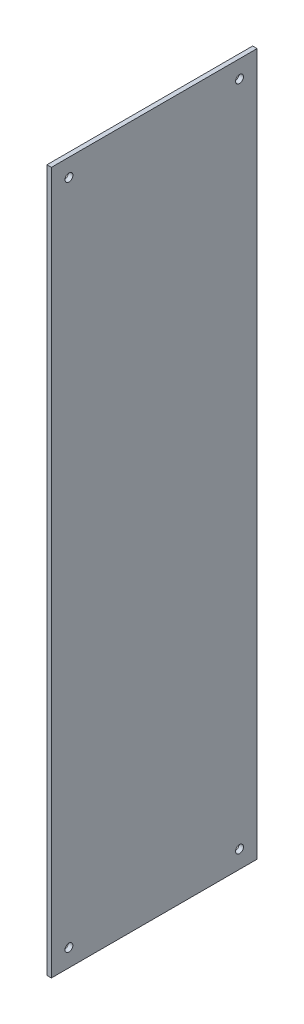
SolidWorks part; units mm, degrees
ref_plane "Front Plane" through (0, 0, 0) normal (1, 0, 0) x (0, 1, 0)
ref_plane "Top Plane" through (0, 0, 0) normal (0, 0, 1) x (0, 1, 0)
ref_plane "Right Plane" through (0, 0, 0) normal (0, 1, 0) x (-1, 0, 0)
sketch "Sketch1" plane through (0, 0, 0) normal (1, 0, 0) x (0, 1, 0)
  line L1 (-250, -73.25) -> (250, -73.25)
  line L2 (-250, -73.25) -> (-250, 73.25)
  line L3 (-250, 73.25) -> (250, 73.25)
  line L4 (250, -73.25) -> (250, 73.25)
  line L5 (-250, -73.25) -> (250, 73.25) construction
  line L6 (-250, 73.25) -> (250, -73.25) construction
  line L7 (237.5, -60.75) -> (-237.5, -60.75) construction
  line L8 (237.5, -60.75) -> (237.5, 60.75) construction
  line L9 (237.5, 60.75) -> (-237.5, 60.75) construction
  line L10 (-237.5, -60.75) -> (-237.5, 60.75) construction
  line L11 (237.5, -60.75) -> (-237.5, 60.75) construction
  line L12 (237.5, 60.75) -> (-237.5, -60.75) construction
  circle A0 centre (-237.5, 60.75) radius 2.8
  circle A1 centre (-237.5, -60.75) radius 2.8
  circle A2 centre (237.5, 60.75) radius 2.8
  circle A3 centre (237.5, -60.75) radius 2.8
  point P0 (0, 0)
  point P6 (0, 0)
  dimension "D3" = 5.6
  dimension "D1" = 146.5
  dimension "D2" = 500
  dimension "D4" = 12.5
  dimension "D5" = 12.5
extrude "Boss-Extrude1" add sketch "Sketch1" along normal blind 3.175
